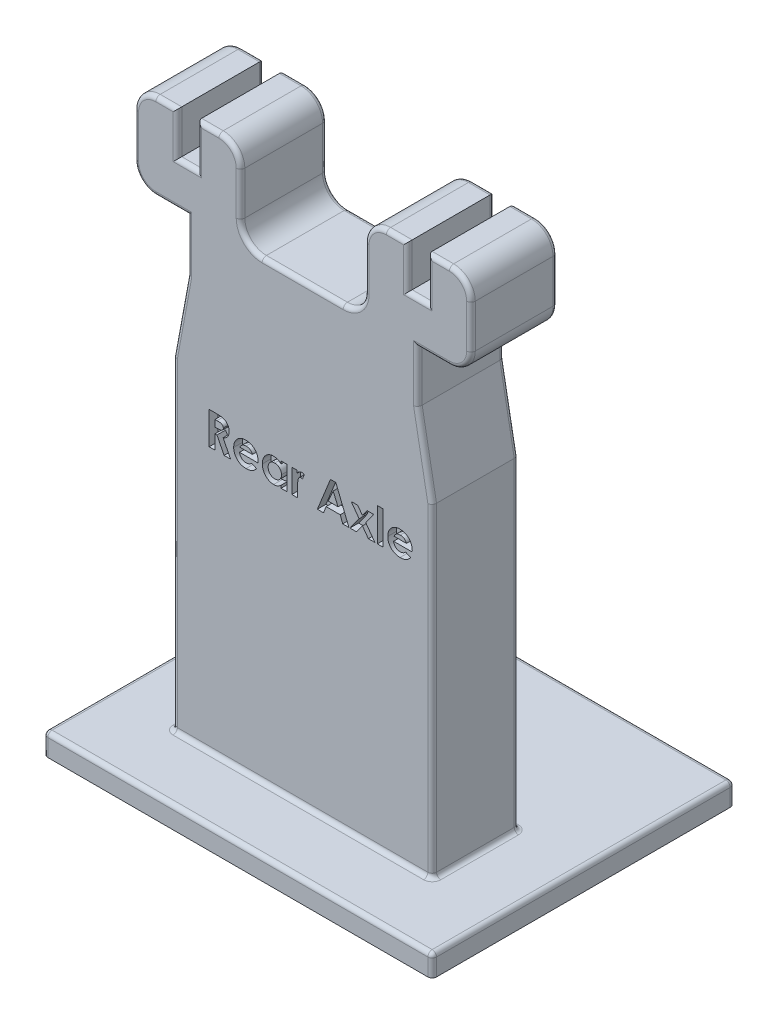
SolidWorks part; units mm, degrees
ref_plane "Front Plane" through (0, 0, 0) normal (0, 0, 1) x (1, 0, 0)
ref_plane "Top Plane" through (0, 0, 0) normal (0, 1, 0) x (1, 0, 0)
ref_plane "Right Plane" through (0, 0, 0) normal (1, 0, 0) x (0, 0, -1)
sketch "Sketch1" plane through (0, 0, 0) normal (0, 1, 0) x (1, 0, 0)
  line L1 (0, 0) -> (-114.3, 0)
  line L2 (0, 0) -> (0, 88.9)
  line L3 (0, 88.9) -> (-114.3, 88.9)
  line L4 (-114.3, 0) -> (-114.3, 88.9)
  dimension "D1" = 114.3
  dimension "D2" = 88.9
extrude "Boss-Extrude1" add sketch "Sketch1" along normal blind 6.35
sketch "Sketch2" plane through (0, 6.35, 0) normal (0, 1, 0) x (1, 0, 0)
  line L0 (0, 88.9) -> (-114.3, 88.9) construction
  line L1 (-95.25, 44.45) -> (-19.05, 44.45)
  line L2 (-95.25, 44.45) -> (-95.25, 19.05)
  line L3 (-95.25, 19.05) -> (-19.05, 19.05)
  line L4 (-19.05, 44.45) -> (-19.05, 19.05)
  line L5 (-114.3, 0) -> (0, 0) construction
  point P4 (-57.15, 88.9)
  point P5 (-57.15, 44.45)
  dimension "D1" = 76.2
  dimension "D2" = 19.05
  dimension "D3" = 25.4
extrude "Boss-Extrude2" add sketch "Sketch2" along normal blind 101.6 from surface at -6.35 starting at face at (-57.15, 0, -44.45)
sketch "Sketch3" plane through (0, 0, -19.05) normal (0, 0, 1) x (1, 0, 0)
  line L0 (-93.9546, 165.1) -> (-93.9546, 152.4)
  line L1 (-93.9546, 152.4) -> (-88.1126, 152.4)
  line L2 (-88.1126, 152.4) -> (-88.1126, 165.1)
  line L3 (-114.3, 0) -> (0, 0) construction
  line L4 (-57.15, 6.35) -> (-57.15, 216.4128) construction
  line L5 (-114.3, 6.35) -> (0, 6.35) construction
  line L6 (-26.1874, 152.4) -> (-26.1874, 165.1)
  line L7 (-20.3454, 152.4) -> (-26.1874, 152.4)
  line L8 (-20.3454, 165.1) -> (-20.3454, 152.4)
  line L9 (-106.6546, 165.1) -> (-106.6546, 139.7)
  line L10 (-106.6546, 139.7) -> (-75.4126, 139.7)
  line L11 (-75.4126, 139.7) -> (-75.4126, 165.1)
  line L12 (-7.6454, 165.1) -> (-7.6454, 139.7)
  line L13 (-7.6454, 139.7) -> (-38.8874, 139.7)
  line L14 (-38.8874, 139.7) -> (-38.8874, 165.1)
  line L15 (-106.6546, 165.1) -> (-93.9546, 165.1)
  line L16 (-88.1126, 165.1) -> (-75.4126, 165.1)
  line L17 (-38.8874, 165.1) -> (-26.1874, 165.1)
  line L18 (-20.3454, 165.1) -> (-7.6454, 165.1)
  line L19 (-91.0336, 124.46) -> (-95.25, 101.6)
  line L20 (-91.0336, 139.7) -> (-23.2664, 139.7)
  line L21 (-91.0336, 139.7) -> (-91.0336, 124.46)
  line L22 (-91.0336, 124.46) -> (-23.2664, 124.46)
  line L23 (-23.2664, 139.7) -> (-23.2664, 124.46)
  line L24 (-95.25, 101.6) -> (-19.05, 101.6)
  line L25 (-19.05, 101.6) -> (-23.2664, 124.46)
  point P5 (-91.0336, 152.4)
  point P27 (-23.2664, 139.7)
  line M11 (-19.05, 101.6) -> (-95.25, 101.6)
  dimension "D1" = 5.842
  dimension "D2" = 12.7
  dimension "D3" = 152.4
  dimension "D4" = 33.8836
  dimension "D7" = 15.24
  dimension "D5" = 12.7
  dimension "D6" = 12.7
extrude "Boss-Extrude3" add sketch "Sketch3" against normal up to surface (25.4 mm away) contours L24 L4 L22 L19 | L4 L25 L22 M11 | L22 L4 L20 L10 L21 | L4 L22 L23 L13 L20 | L16 L2 L1 L0 L15 L9 L10 L11 | L18 L8 L7 L6 L17 L14 L13 L12 up to face at (-57.15, 53.975, -44.45)
fillet "Fillet1" radius 6.35 8 edges at (-7.6454, 139.7, -31.75) (-7.6454, 165.1, -31.75) (-38.8874, 165.1, -31.75) (-38.8874, 139.7, -31.75) (-75.4126, 139.7, -31.75) (-75.4126, 165.1, -31.75) (-106.6546, 165.1, -31.75) (-106.6546, 139.7, -31.75)
fillet "Fillet2" radius 1.27 66 edges at (-104.7947, 141.5599, -44.45) (-104.7947, 163.2401, -44.45) (-77.2725, 163.2401, -44.45) (-9.5053, 163.2401, -44.45) (-9.5053, 141.5599, -44.45) (-37.0275, 163.2401, -44.45) (-40.7473, 141.5599, -19.05) (-40.7473, 141.5599, -44.45) (-73.5527, 141.5599, -19.05) (-73.5527, 141.5599, -44.45) (-57.15, 6.35, -44.45) (-95.25, 6.35, -31.75) (-57.15, 6.35, -19.05) (-19.05, 6.35, -31.75) (-19.05, 53.975, -44.45) (-95.25, 53.975, -44.45) (-95.25, 53.975, -19.05) (-19.05, 53.975, -19.05) (-21.1582, 113.03, -19.05) (-20.3454, 158.75, -19.05) (-23.2664, 152.4, -19.05) (-26.1874, 158.75, -19.05) (-91.0336, 132.08, -19.05) (-93.1418, 113.03, -19.05) (-23.2664, 132.08, -44.45) (-23.2664, 132.08, -19.05) (-18.6309, 139.7, -44.45) (-17.1704, 165.1, -19.05) (-29.3624, 165.1, -44.45) (-84.9376, 165.1, -19.05) (-88.1126, 158.75, -44.45) (-88.1126, 158.75, -19.05) (-91.0336, 152.4, -44.45) (-91.0336, 152.4, -19.05) (-93.9546, 158.75, -44.45) (-93.9546, 158.75, -19.05) (-97.1296, 165.1, -44.45) (-21.1582, 113.03, -44.45) (-93.1418, 113.03, -44.45) (-91.0336, 132.08, -44.45) (-95.6691, 139.7, -44.45) (-26.1874, 158.75, -44.45) (-23.2664, 152.4, -44.45) (-20.3454, 158.75, -44.45) (-29.3624, 165.1, -19.05) (-18.6309, 139.7, -19.05) (-7.6454, 152.4, -19.05) (-38.8874, 152.4, -19.05) (-57.15, 139.7, -19.05) (-75.4126, 152.4, -19.05) (-97.1296, 165.1, -19.05) (-106.6546, 152.4, -19.05) (-95.6691, 139.7, -19.05) (-104.7947, 141.5599, -19.05) (-104.7947, 163.2401, -19.05) (-77.2725, 163.2401, -19.05) (-9.5053, 163.2401, -19.05) (-9.5053, 141.5599, -19.05) (-37.0275, 163.2401, -19.05) (-38.8874, 152.4, -44.45) (-106.6546, 152.4, -44.45) (-84.9376, 165.1, -44.45) (-75.4126, 152.4, -44.45) (-57.15, 139.7, -44.45) (-17.1704, 165.1, -44.45) (-7.6454, 152.4, -44.45)
fillet "Fillet3" radius 1.27 8 edges at (-114.3, 6.35, -44.45) (-57.15, 6.35, 0) (0, 6.35, -44.45) (-57.15, 6.35, -88.9) (-114.3, 3.175, -88.9) (0, 3.175, -88.9) (0, 3.175, 0) (-114.3, 3.175, 0)
sketch "Sketch4" plane through (0, 0, -19.05) normal (0, 0, 1) x (1, 0, 0)
  line L0 (-85.725, 83.82) -> (-28.575, 83.82) construction
  line L1 (-93.98, 7.62) -> (-20.32, 7.62) construction
  text T0 "<b>Rear Axle</b>" font "Century Gothic" height in points 36
  point P2 (-57.15, 83.82)
  point P3 (-57.15, 7.62)
  dimension "D1" = 57.15
  dimension "D2" = 76.2
extrude "Cut-Extrude1" cut sketch "Sketch4" against normal blind 2.54
